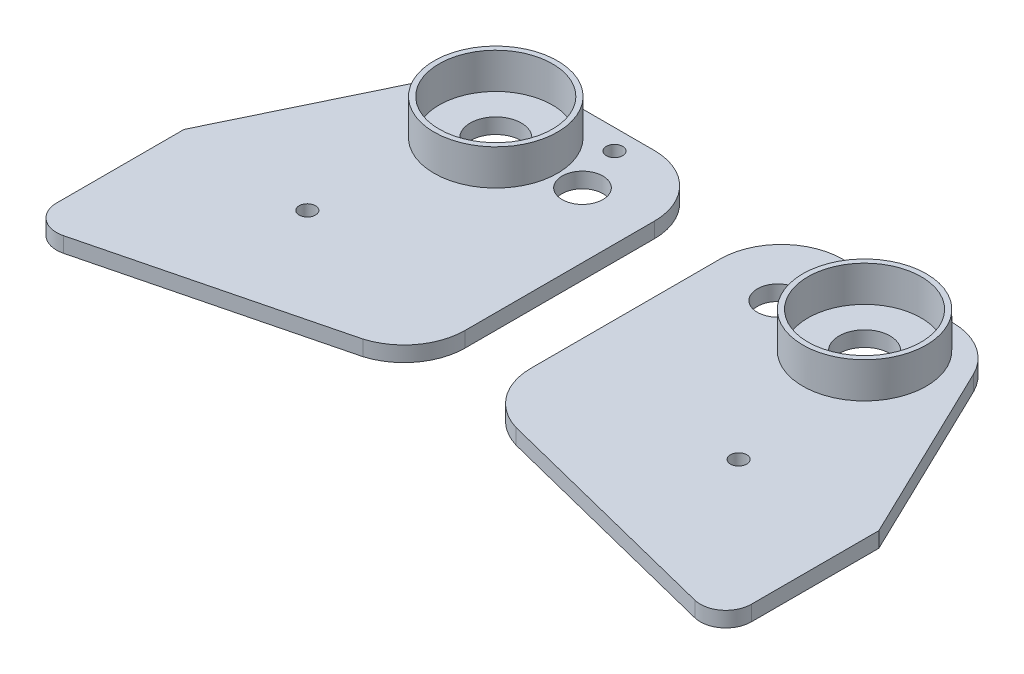
SolidWorks part; units mm, degrees
ref_plane "Ön Düzlem" through (0, 0, 0) normal (0, 0, 1) x (1, 0, 0)
ref_plane "Üst Düzlem" through (0, 0, 0) normal (0, 1, 0) x (1, 0, 0)
ref_plane "Sağ Düzlem" through (0, 0, 0) normal (1, 0, 0) x (0, 0, -1)
sketch "Çizim1" plane through (0, 0, 0) normal (0, 1, 0) x (1, 0, 0)
  line L0 (-68.0843, 1.7039) -> (-68.0848, -23.2865)
  line L1 (-6.4354, 1.691) -> (-6.4355, -4.8454)
  line L2 (-6.4354, 1.691) -> (-6.4351, 32.2162)
  line L3 (-18.4349, 44.2163) -> (-40.0427, 44.2166)
  line L4 (-61.8647, -28.1355) -> (-14.9999, -16.3429)
  line L5 (-50.7602, 37.6146) -> (-68.0843, 1.7039)
  line L6 (0, 67.3649) -> (0, -73.0349) construction
  line L7 (50.7602, 37.6146) -> (68.0843, 1.7039)
  line L8 (61.8647, -28.1355) -> (14.9999, -16.3429)
  line L9 (18.4349, 44.2163) -> (40.0427, 44.2166)
  line L10 (6.4354, 1.691) -> (6.4351, 32.2162)
  line L11 (6.4354, 1.691) -> (6.4355, -4.8454)
  line L12 (68.0843, 1.7039) -> (68.0848, -23.2865)
  arc A0 (-14.9999, -16.3429) -> (-6.4355, -4.8454) centre (-18.4355, -4.8452) ccw
  arc A1 (-68.0848, -23.2865) -> (-61.8647, -28.1355) centre (-63.0848, -23.2866) ccw
  arc A2 (-6.4351, 32.2162) -> (-18.4349, 44.2163) centre (-18.4351, 32.2163) ccw
  arc A3 (-40.0427, 44.2166) -> (-50.7602, 37.6146) centre (-40.0429, 32.2166) ccw
  circle A4 centre (-36.1355, 30.846) radius 5
  circle A5 centre (-19.1355, 30.8419) radius 4
  circle A6 centre (-42.2605, 0.0416) radius 1.6
  circle A7 centre (42.2605, 0.0416) radius 1.6
  circle A8 centre (19.1355, 30.8419) radius 4
  circle A9 centre (36.1355, 30.846) radius 5
  arc A10 (40.0427, 44.2166) -> (50.7602, 37.6146) centre (40.0429, 32.2166) cw
  arc A11 (6.4351, 32.2162) -> (18.4349, 44.2163) centre (18.4351, 32.2163) cw
  arc A12 (14.9999, -16.3429) -> (6.4355, -4.8454) centre (18.4355, -4.8452) cw
  arc A13 (68.0848, -23.2865) -> (61.8647, -28.1355) centre (63.0848, -23.2866) cw
  dimension "D1" = 5
extrude "Yükseklik-Ekstrüzyon2" add sketch "Çizim1" along normal blind 3
sketch "Çizim2" plane through (0, 3, 0) normal (0, 1, 0) x (1, 0, 0)
  circle A0 centre (-36.1355, 30.846) radius 11.1
  circle A1 centre (-36.1355, 30.846) radius 12.1
extrude "Yükseklik-Ekstrüzyon3" add sketch "Çizim2" along normal blind 7
sketch "Çizim3" plane through (0, 3, 0) normal (0, 1, 0) x (1, 0, 0)
  circle A0 centre (36.1355, 30.846) radius 11.1
  circle A1 centre (36.1355, 30.846) radius 12.1
extrude "Yükseklik-Ekstrüzyon4" add sketch "Çizim3" along normal blind 7
sketch "Çizim4" plane through (0, 3, 0) normal (0, 1, 0) x (1, 0, 0)
  line L0 (-29.2388, 44.2165) -> (-29.2388, -14.5849) construction
  line L1 (-18.4349, 44.2163) -> (-40.0427, 44.2166) construction
  circle A0 centre (-22.2388, 40.2164) radius 1.6
  point P6 (0, 0)
  point P8 (-21.4772, 44.2164)
  dimension "D1" = 3.2
  dimension "D2" = 7
  dimension "D3" = 4
extrude "Kes-Ekstrüzyon1" cut sketch "Çizim4" against normal through all
sketch "Çizim5" plane through (0, 3, 0) normal (0, 1, 0) x (1, 0, 0)
  line L0 (29.2388, 44.2165) -> (29.2388, -9.1996) construction
  line L1 (40.0427, 44.2166) -> (18.4349, 44.2163) construction
  circle A0 centre (22.2388, 40.2164) radius 1.6
  dimension "D1" = 3.2
  dimension "D2" = 7
  dimension "D3" = 4
extrude "Kes-Ekstrüzyon2" cut sketch "Çizim5" against normal through all
